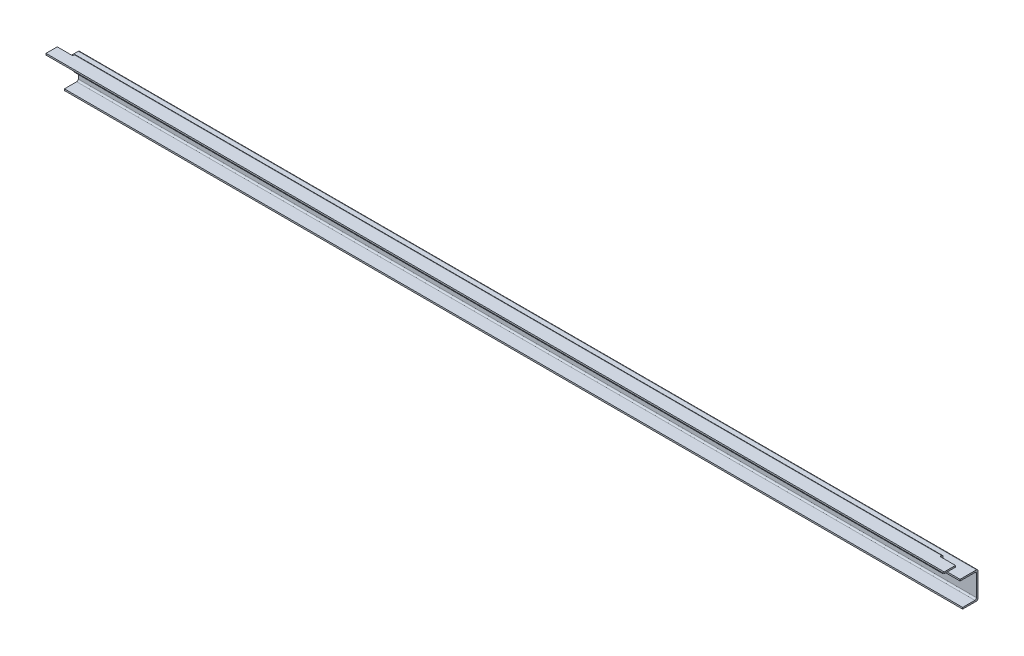
SolidWorks part; units mm, degrees
ref_plane "Front Plane" through (0, 0, 0) normal (0, 0, 1) x (1, 0, 0)
ref_plane "Top Plane" through (0, 0, 0) normal (0, 1, 0) x (1, 0, 0)
ref_plane "Right Plane" through (0, 0, 0) normal (1, 0, 0) x (0, 0, -1)
sketch "Sketch3" plane through (0, 0, 0) normal (1, 0, 0) x (0, 0, -1)
  line L0 (0, 0) -> (28, 0)
  line L1 (28, 0) -> (28, -28)
  line L2 (28, -28) -> (66, -28)
  line L3 (66, -28) -> (66, -81)
  line L12 (0, -3) -> (25, -3)
  line L13 (25, -3) -> (25, -31)
  line L14 (25, -31) -> (63, -31)
  line L15 (66, -81) -> (36, -81)
  line L16 (63, -31) -> (63, -78)
  line L17 (63, -78) -> (36, -78)
  line L18 (0, 0) -> (0, -3)
  line L19 (36, -78) -> (36, -81)
  dimension "D1" = 53
  dimension "D2" = 28
  dimension "D3" = 38
  dimension "D4" = 28
  dimension "D5" = 30
  dimension "D6" = 3
extrude "Boss-Extrude1" add sketch "Sketch3" along normal blind 1754
fillet "Fillet2" radius 3 8 edges at (877, -78, -63) (877, -31, -63) (877, -31, -25) (877, -3, -25) (877, -81, -66) (877, -28, -66) (877, -28, -28) (877, 0, -28)
sketch "Sketch8" plane through (0, 0, -28) normal (0, 0, -1) x (-1, 0, 0)
  line L0 (0, 0) -> (-30, 0)
  line L1 (-1754, 0) -> (0, 0) construction
  line L2 (-30, 0) -> (-30, -31)
  line L3 (0, -31) -> (-1754, -31) construction
  line L4 (-30, -31) -> (0, -31)
  line L5 (0, -31) -> (0, 0)
  line L6 (-1754, 0) -> (-1724, 0)
  line L11 (-1754, 0) -> (-1754, -31)
  line L12 (-1754, -31) -> (-1724, -31)
  line L13 (-1724, -31) -> (-1724, 0)
  dimension "D1" = 30
  dimension "D2" = 30
extrude "Cut-Extrude4" cut sketch "Sketch8" along normal blind 3 and the other way blind 6
equation "\"rear_door_bottom_BB_3mm_length\"=1754"
equation "\"D1@Boss-Extrude1\"= \"boxWidth\" - 88 - 88"
equation "\"CarBeamWidth\"=700.0"
equation "\"WheelWidth\"=650.0"
equation "\"Wheel_FrontBoxDistance\"=1390.0"
equation "\"boxLength\"=5100.0"
equation "\"boxWidth\"=1930.0"
equation "\"MetalSheet_3mm_length\"=5030.0"
equation "\"MetalSheet_3mm_width\"=1923.0"
equation "\"MetalSheet_3mm_FloorCut_L_length\"=1764.0"
equation "\"MetalSheet_3mm_FloorCut_L_disdance\"=1665.0"
equation "\"MetalSheet_3mm_FloorCut_R_length\"=1764.0"
equation "\"MetalSheet_3mm_FloorCut_R_disdance\"=1665.0"
equation "\"indoorHeight\"=1940.0"
equation "\"indoorHeight_para\"=25.0"
equation "\"rearLightHeight_para\"=265.0"
equation "\"doorColumnBar_A_FR_3mm_length_Cut\"=2310.0"
equation "\"A\"=0.0"
equation "\"haveDoor_R\"=1"
equation "\"side_door_bottom_R_3mm_length\"=1934.0"
equation "\"side_door_bottom_R_3mm_toFrontDistance\"=1583.0"
equation "\"1Bar_Side_RF_3mm_length\"=1493.0"
equation "\"1Bar_Side_RB_3mm_length\"=1493.0"
equation "\"DoorSeparator_RF_3mm_withHinge_toFrontDistance\"=1673.0"
equation "\"DoorSeparator_RF_3mm_withHinge_exist\"=1"
equation "\"DoorSeparator_RB_3mm_withHinge_toFrontDistance\"=3427.0"
equation "\"DoorSeparator_RB_3mm_withHinge_exist\"=1"
equation "\"Door_R1_L_open_Single_toFrontDistance\"=2547.5"
equation "\"Door_R1_L_open_Single_exist\"=1"
equation "\"door_base_long7_R1_L_open_Single_height\"=1890.0"
equation "\"door_base_short7_R1_L_open_Single_height\"=1890.0"
equation "\"door_base_short7_R1_L_open_Single_width\"=864"
equation "\"Door_R1_R_open_Single_toFrontDistance\"=3422.0"
equation "\"Door_R1_R_open_Single_exist\"=1"
equation "\"door_base_long7_R1_R_open_Single_height\"=1890.0"
equation "\"door_base_short7_R1_R_open_Single_height\"=1890.0"
equation "\"door_base_short7_R1_R_open_Single_width\"=864"
equation "\"x\"=66.0"
equation "\"door_base_double_BL_height\"=1890.0"
equation "\"door_base_short7_BL_Single_height\"=1890.0"
equation "\"door_base_short7_BL_Single_width\"=864"
equation "\"door_base_long7_BR_Single_height\"=1890.0"
equation "\"door_base_short7_BR_Single_height\"=1890.0"
equation "\"door_base_short7_BR_Single_width\"=864"
equation "\"da\"=62.0"
equation "\"SquareTube_length\"=1923.0"
equation "\"channelSteel_length\"=5030.0"
equation "\"SquareTube_inFront_AvgDistance\"=285.0"
equation "\"SquareTube_inFront_TotalCount\"=5"
equation "\"SquareTube_inFront1_cutDepth50_R\"=0.5"
equation "\"SquareTube_inFront1_cutDepth50_L\"=0.5"
equation "\"SquareTube_inFront2_cutDepth50_R\"=0.5"
equation "\"SquareTube_inFront2_cutDepth50_L\"=0.5"
equation "\"SquareTube_inFront3_cutDepth50_R\"=0.5"
equation "\"SquareTube_inFront3_cutDepth50_L\"=0.5"
equation "\"SquareTube_inFront4_cutDepth50_R\"=0.5"
equation "\"SquareTube_inFront4_cutDepth50_L\"=0.5"
equation "\"SquareTube_inFront5_cutDepth50_R\"=50"
equation "\"SquareTube_inFront5_cutDepth50_L\"=50"
equation "\"SquareTube_inFront6_cutDepth50_R\"=50"
equation "\"SquareTube_inFront6_cutDepth50_L\"=50"
equation "\"SquareTube_inFront7_cutDepth50_R\"=50"
equation "\"SquareTube_inFront7_cutDepth50_L\"=50"
equation "\"SquareTube_inFront8_cutDepth50_R\"=50"
equation "\"SquareTube_inFront8_cutDepth50_L\"=50"
equation "\"SquareTube_inFront9_cutDepth50_R\"=50"
equation "\"SquareTube_inFront9_cutDepth50_L\"=50"
equation "\"SquareTube_inFront10_cutDepth50_R\"=50"
equation "\"SquareTube_inFront10_cutDepth50_L\"=50"
equation "\"SquareTube_inFront11_cutDepth50_R\"=50"
equation "\"SquareTube_inFront11_cutDepth50_L\"=50"
equation "\"SquareTube_inFront12_cutDepth50_R\"=50"
equation "\"SquareTube_inFront12_cutDepth50_L\"=50"
equation "\"SquareTube_inFront13_cutDepth50_R\"=50"
equation "\"SquareTube_inFront13_cutDepth50_L\"=50"
equation "\"SquareTube_inFront14_cutDepth50_R\"=50"
equation "\"SquareTube_inFront14_cutDepth50_L\"=50"
equation "\"SquareTube_inBack_AvgDistance\"=333.125"
equation "\"SquareTube_inBack_TotalCount\"=9"
equation "\"SquareTube_inBack1_cutDepth50_R\"=50"
equation "\"SquareTube_inBack1_cutDepth50_L\"=50"
equation "\"SquareTube_inBack2_cutDepth50_R\"=50"
equation "\"SquareTube_inBack2_cutDepth50_L\"=50"
equation "\"SquareTube_inBack3_cutDepth50_R\"=50"
equation "\"SquareTube_inBack3_cutDepth50_L\"=50"
equation "\"SquareTube_inBack4_cutDepth50_R\"=50"
equation "\"SquareTube_inBack4_cutDepth50_L\"=50"
equation "\"SquareTube_inBack5_cutDepth50_R\"=50"
equation "\"SquareTube_inBack5_cutDepth50_L\"=50"
equation "\"SquareTube_inBack6_cutDepth50_R\"=0.5"
equation "\"SquareTube_inBack6_cutDepth50_L\"=0.5"
equation "\"SquareTube_inBack7_cutDepth50_R\"=0.5"
equation "\"SquareTube_inBack7_cutDepth50_L\"=0.5"
equation "\"SquareTube_inBack8_cutDepth50_R\"=0.5"
equation "\"SquareTube_inBack8_cutDepth50_L\"=0.5"
